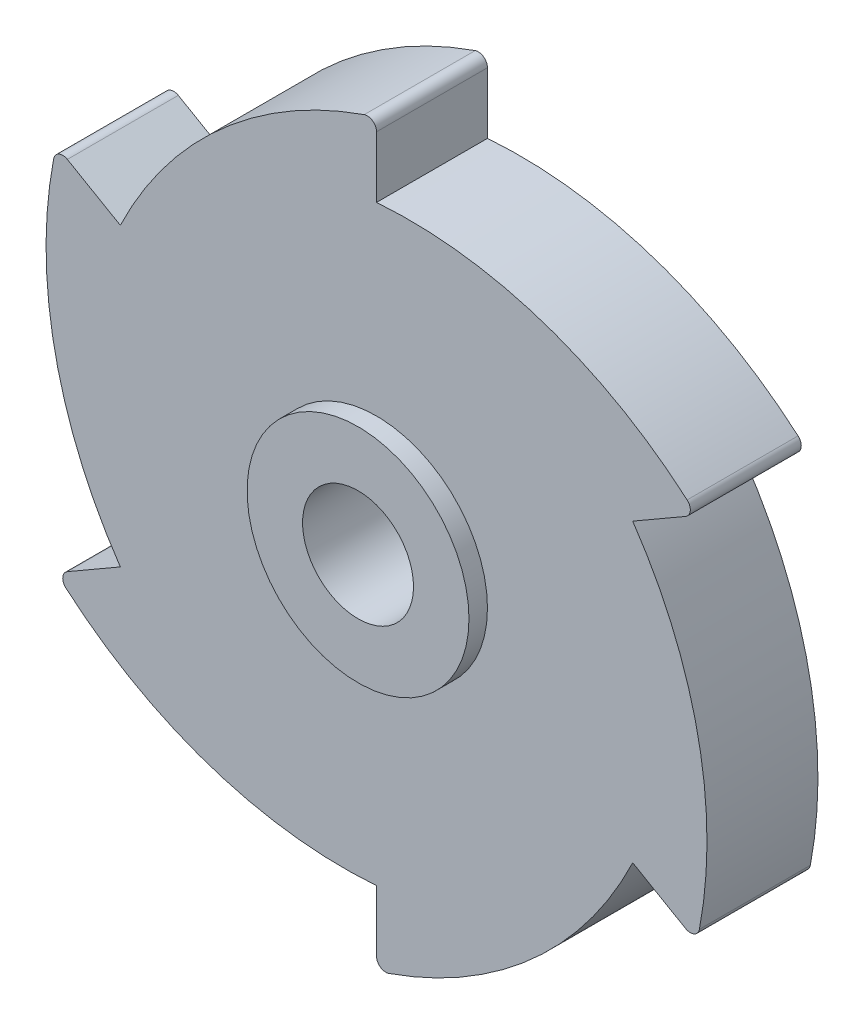
SolidWorks part; units mm, degrees
material "ABS"
ref_plane "Front Plane" through (0, 0, 0) normal (0, 0, 1) x (1, 0, 0)
ref_plane "Top Plane" through (0, 0, 0) normal (0, 1, 0) x (1, 0, 0)
ref_plane "Right Plane" through (0, 0, 0) normal (1, 0, 0) x (0, 0, -1)
sketch "Sketch1" plane through (0, 0, 0) normal (0, 0, 1) x (1, 0, 0)
  circle A0 centre (0, 0) radius 20
  dimension "D1" = 40
extrude "Boss-Extrude1" add sketch "Sketch1" along normal blind 6
sketch "Sketch2" plane through (0, 0, 6) normal (0, 0, 1) x (1, 0, 0)
  line L0 (0, 0) -> (0, 32) construction
  line L1 (0, 16) -> (0, 20)
  line L2 (0, 0) -> (22.5171, 13.0002) construction
  circle A0 centre (0, 0) radius 16 construction
  arc A1 (17.3205, 10) -> (0, 16) centre (1.7553, -6.9329) ccw
  circle A2 centre (0, 0) radius 20 construction
  arc A3 (0, 20) -> (17.3205, 10) centre (0, 0) cw
  dimension "D1" = 32
  dimension "D3" = 23
  dimension "D2" = 60
extrude "Cut-Extrude1" cut sketch "Sketch2" against normal through all both and the other way through all
pattern_circular "CirPattern1" count 6 over 360 about axis through (0, 0, 0) along (0, 0, 1) of "Cut-Extrude1"
fillet "Fillet1" radius 0.5 6 edges at (0, -20, 3) (-17.3205, -10, 3) (-17.3205, 10, 3) (17.3205, -10, 3) (17.3205, 10, 3) (0, 20, 3)
sketch "Sketch4" plane through (0, 0, 0) normal (0, 0, 1) x (1, 0, 0)
  circle A0 centre (0, 0) radius 6.0146
extrude "Boss-Extrude2" add sketch "Sketch4" along normal blind 1
sketch "Sketch8" plane through (0, 0, 6) normal (0, 0, 1) x (1, 0, 0)
  circle A0 centre (0, 0) radius 6
  dimension "D1" = 12
extrude "Boss-Extrude3" add sketch "Sketch8" along normal blind 1
sketch "Sketch9" plane through (0, 0, 0) normal (0, 0, -1) x (-1, 0, 0)
  circle A0 centre (0, 0) radius 6
  dimension "D1" = 12
extrude "Cut-Extrude3" cut sketch "Sketch9" against normal blind 1
sketch "Sketch10" plane through (0, 0, 7) normal (0, 0, 1) x (1, 0, 0)
  circle A0 centre (0, 0) radius 3
  dimension "D1" = 6
extrude "Cut-Extrude4" cut sketch "Sketch10" against normal through all both
